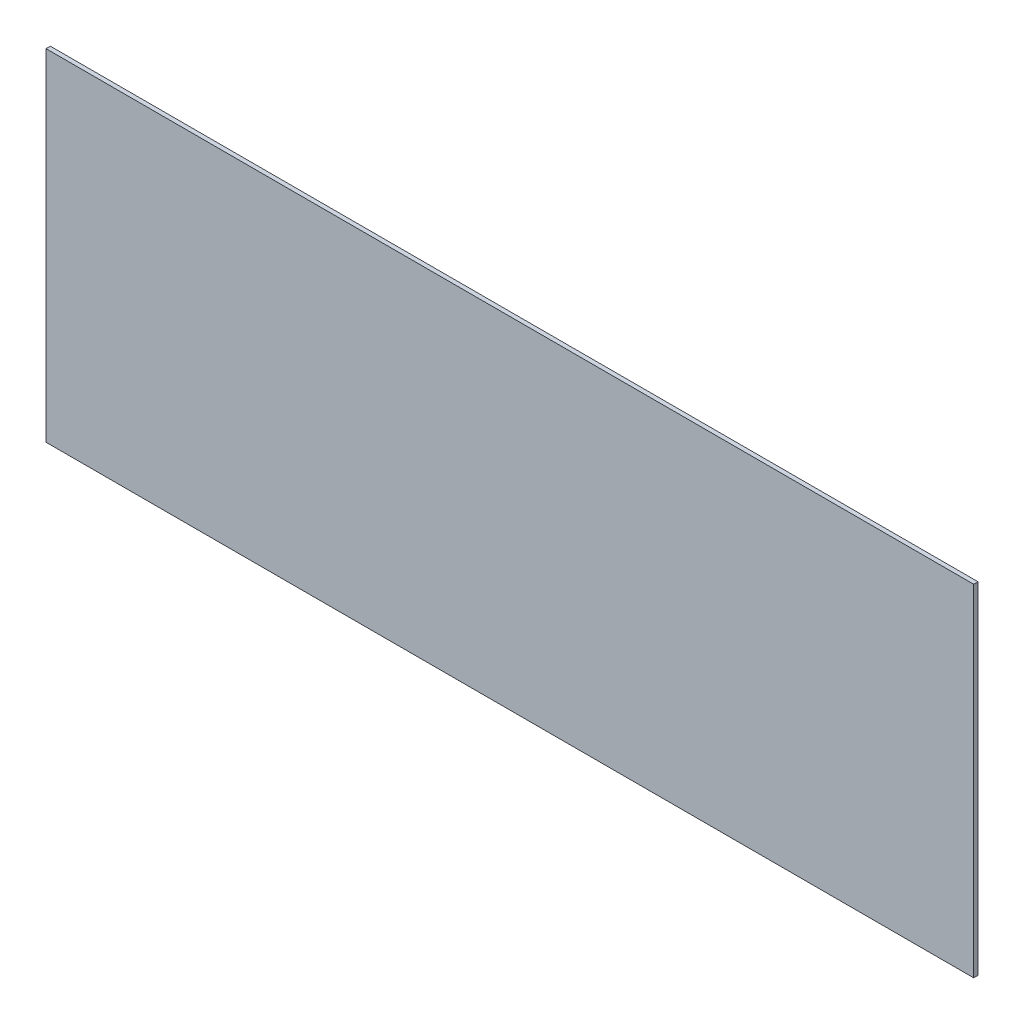
SolidWorks part; units mm, degrees
ref_plane "Front Plane" through (0, 0, 0) normal (0, 0, 1) x (1, 0, 0)
ref_plane "Top Plane" through (0, 0, 0) normal (0, 1, 0) x (1, 0, 0)
ref_plane "Right Plane" through (0, 0, 0) normal (1, 0, 0) x (0, 0, -1)
sketch "Sketch2" plane through (0, 0, 0) normal (0, 0, 1) x (1, 0, 0)
  line L0 (-9.525, 139.0036) -> (420.475, 139.0036)
  line L1 (420.475, 139.0036) -> (420.475, -19.0036)
  line L2 (420.475, -19.0036) -> (-9.525, -19.0036)
  line L3 (-9.525, -19.0036) -> (-9.525, 139.0036)
extrude "Boss-Extrude1" add sketch "Sketch2" along normal blind 2
